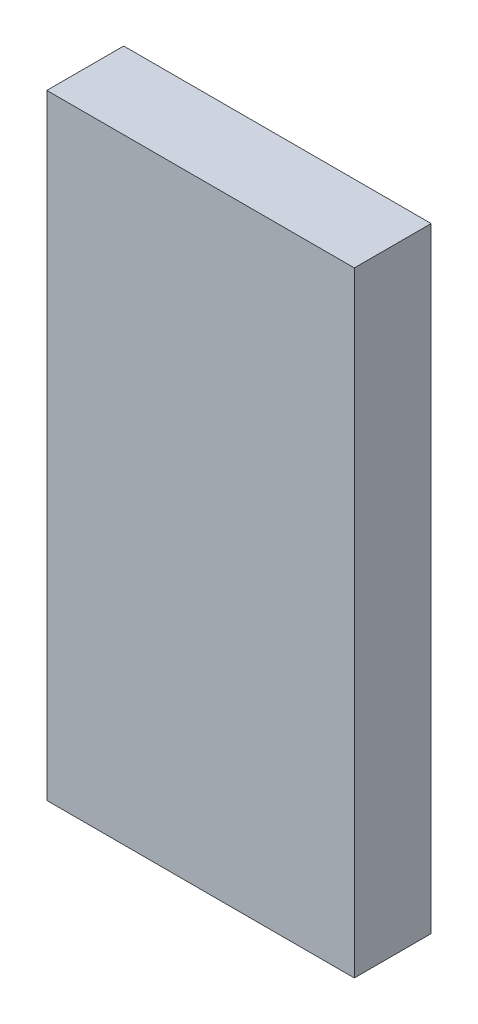
SolidWorks part; units mm, degrees
material "Nickel"
ref_plane "Front Plane" through (0, 0, 0) normal (0, 0, 1) x (1, 0, 0)
ref_plane "Top Plane" through (0, 0, 0) normal (0, 1, 0) x (1, 0, 0)
ref_plane "Right Plane" through (0, 0, 0) normal (1, 0, 0) x (0, 0, -1)
sketch "Sketch1" plane through (0, 0, 0) normal (0, 0, 1) x (1, 0, 0)
  line L1 (-3.175, -6.35) -> (3.175, -6.35)
  line L2 (-3.175, -6.35) -> (-3.175, 6.35)
  line L3 (-3.175, 6.35) -> (3.175, 6.35)
  line L4 (3.175, -6.35) -> (3.175, 6.35)
  line L5 (-3.175, -6.35) -> (3.175, 6.35) construction
  line L6 (-3.175, 6.35) -> (3.175, -6.35) construction
  point P0 (0, 0)
  dimension "D1" = 12.7
  dimension "D2" = 6.35
extrude "Boss-Extrude1" add sketch "Sketch1" along normal blind 1.5875
